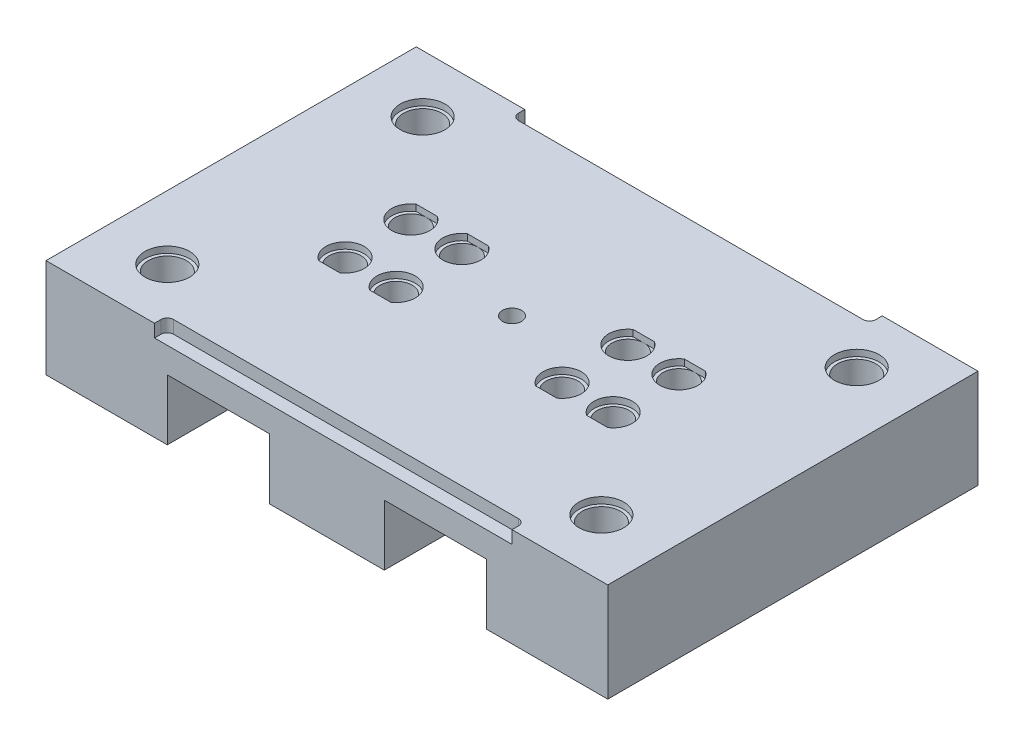
SolidWorks part; units mm, degrees
ref_plane "Front Plane" through (0, 0, 0) normal (0, 0, 1) x (1, 0, 0)
ref_plane "Top Plane" through (0, 0, 0) normal (0, 1, 0) x (1, 0, 0)
ref_plane "Right Plane" through (0, 0, 0) normal (1, 0, 0) x (0, 0, -1)
sketch "Sketch1" plane through (0, 0, 0) normal (0, 1, 0) x (1, 0, 0)
  line L1 (-440, 290) -> (440, 290)
  line L2 (-440, 290) -> (-440, -290)
  line L3 (-440, -290) -> (440, -290)
  line L4 (440, 290) -> (440, -290)
  line L6 (-440, 0) -> (440, 0) construction
  point P0 (0, 0)
extrude "Boss-Extrude1" add sketch "Sketch1" along normal blind 155
sketch "Sketch2" plane through (0, 0, 290) normal (0, 0, 1) x (1, 0, 0)
  line L0 (-440, 0) -> (440, 0) construction
  line L1 (-250, 0) -> (-90, 0)
  line L2 (-250, 0) -> (-250, 95)
  line L3 (-250, 95) -> (-90, 95)
  line L4 (-90, 0) -> (-90, 95)
  line L5 (-440, 155) -> (-440, 0) construction
  line L6 (-440, 155) -> (440, 155) construction
  dimension "D1" = 190
  dimension "D2" = 160
  dimension "D3" = 60
extrude "Cut-Extrude1" cut sketch "Sketch2" against normal blind 705
mirror "Mirror1" about plane through (0, 0, 0) normal (1, 0, 0) of "Cut-Extrude1"
sketch "Sketch3" plane through (0, 155, 0) normal (0, 1, 0) x (1, 0, 0)
  line L0 (-440, -290) -> (440, -290) construction
  line L1 (-440, 290) -> (-440, -290) construction
  line L2 (-90, 290) -> (-90, -290) construction
  circle A0 centre (-210, -51.5) radius 30
  circle A1 centre (-130, -51.5) radius 30
  point P0 (-210, -51.5)
  point P5 (-130, -51.5)
  dimension "D1" = 238.5
  dimension "D2" = 230
  dimension "D3" = 40
extrude "Cut-Extrude2" cut sketch "Sketch3" against normal blind 10
sketch "Sketch4" plane through (0, 145, 0) normal (0, 1, 0) x (1, 0, 0)
  circle A0 centre (-210, -51.5) radius 25
  circle A1 centre (-130, -51.5) radius 25
extrude "Cut-Extrude3" cut sketch "Sketch4" against normal blind 60
mirror "Mirror2" about plane through (0, 0, 0) normal (1, 0, 0) of "Cut-Extrude3", "Cut-Extrude2"
mirror "Mirror3" about plane through (0, 0, 0) normal (0, 0, 1) of "Mirror2", "Cut-Extrude2", "Cut-Extrude3"
sketch "Sketch5" plane through (0, 155, 0) normal (0, 1, 0) x (1, 0, 0)
  line L1 (-293.4014, 101.8102) -> (284.6843, 101.8102)
  line L2 (-293.4014, 101.8102) -> (-293.4014, 76.5)
  line L3 (-293.4014, 76.5) -> (284.6843, 76.5)
  line L4 (284.6843, 101.8102) -> (284.6843, 76.5)
  dimension "D1" = 76.5
extrude "Boss-Extrude2" add sketch "Sketch5" against normal blind 18
mirror "Mirror4" about plane through (0, 0, 0) normal (0, 0, 1) of "Boss-Extrude2"
sketch "Sketch6" plane through (0, 95, 0) normal (0, -1, 0) x (1, 0, 0)
  line L3 (-200, 150) -> (-140, 150) construction
  line L4 (-200, 165) -> (-140, 165)
  line L5 (-200, 135) -> (-140, 135)
  line L7 (200, 150) -> (140, 150) construction
  line L8 (200, 165) -> (140, 165)
  line L9 (200, 135) -> (140, 135)
  line L10 (200, -150) -> (140, -150) construction
  line L11 (200, -165) -> (140, -165)
  line L12 (200, -135) -> (140, -135)
  line L13 (-200, -150) -> (-140, -150) construction
  line L14 (-200, -165) -> (-140, -165)
  line L15 (-200, -135) -> (-140, -135)
  arc A0 (-200, 165) -> (-200, 135) centre (-200, 150) ccw
  arc A1 (-140, 135) -> (-140, 165) centre (-140, 150) ccw
  arc A2 (200, 165) -> (200, 135) centre (200, 150) cw
  arc A3 (140, 135) -> (140, 165) centre (140, 150) cw
  arc A4 (200, -165) -> (200, -135) centre (200, -150) ccw
  arc A5 (140, -135) -> (140, -165) centre (140, -150) ccw
  arc A6 (-200, -165) -> (-200, -135) centre (-200, -150) cw
  arc A7 (-140, -135) -> (-140, -165) centre (-140, -150) cw
  point P8 (-170, 150)
  point P16 (170, 150)
  point P23 (170, -150)
  point P30 (-170, -150)
  dimension "D1" = 30
  dimension "D2" = 60
extrude "Cut-Extrude5" cut sketch "Sketch6" against normal blind 10
sketch "Sketch7" plane through (0, 0, 0) normal (0, -1, 0) x (1, 0, 0)
  circle A0 centre (0, 0) radius 15
extrude "Cut-Extrude6" cut sketch "Sketch7" against normal blind 440
sketch "Sketch8" plane through (0, 155, 0) normal (0, 1, 0) x (1, 0, 0)
  circle A0 centre (-340, 200) radius 35
  circle A1 centre (340, 200) radius 35
  circle A2 centre (340, -200) radius 35
  circle A3 centre (-340, -200) radius 35
  dimension "D1" = 680
  dimension "D2" = 340
  dimension "D3" = 200
  dimension "D4" = 340
  dimension "D5" = 340
  dimension "D6" = 200
  dimension "D7" = 200
extrude "Cut-Extrude7" cut sketch "Sketch8" against normal blind 10
sketch "Sketch9" plane through (0, 155, 0) normal (0, 1, 0) x (1, 0, 0)
  circle A0 centre (-340, 200) radius 30
  circle A1 centre (340, 200) radius 30
  circle A2 centre (340, -200) radius 30
  circle A3 centre (-340, -200) radius 30
extrude "Cut-Extrude8" cut sketch "Sketch9" against normal blind 413
sketch "Sketch10" plane through (0, 155, 0) normal (0, 1, 0) x (1, 0, 0)
  line L0 (440, 290) -> (-440, 290) construction
  line L1 (-270, 290) -> (290, 290)
  line L2 (-270, 290) -> (-270, 270)
  line L3 (-270, 270) -> (290, 270)
  line L4 (290, 290) -> (290, 270)
  line L5 (-440, 290) -> (-440, -290) construction
  line L6 (440, -290) -> (440, 290) construction
  dimension "D1" = 20
  dimension "D2" = 170
  dimension "D3" = 150
extrude "Cut-Extrude9" cut sketch "Sketch10" against normal blind 20
fillet "Fillet1" radius 10 2 edges at (-270, 145, -270) (290, 145, -270)
mirror "Mirror5" about plane through (0, 0, 0) normal (0, 0, 1) of "Fillet1", "Cut-Extrude9"
